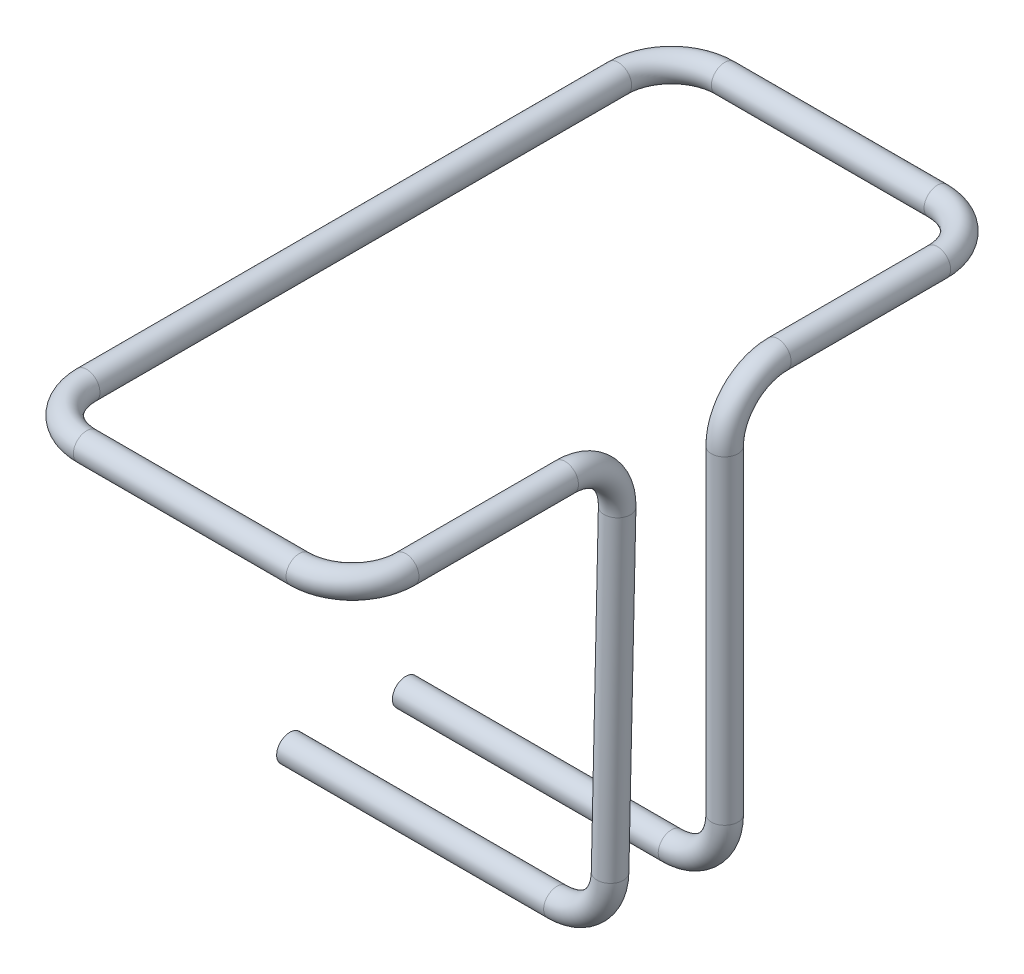
SolidWorks part; units mm, degrees
ref_plane "Front Plane" through (0, 0, 0) normal (0, 0, 1) x (1, 0, 0)
ref_plane "Top Plane" through (0, 0, 0) normal (0, 1, 0) x (1, 0, 0)
ref_plane "Right Plane" through (0, 0, 0) normal (1, 0, 0) x (0, 0, -1)
sketch3d "3DSketch1"
  line L0 (0, 0, 0) -> (2.5109, 0, 0)
  line L1 (3.0108, 0.489, 0) -> (3.0773, 3.4991, 0)
  line L2 (3.0883, 3.999, 0.5) -> (3.0883, 3.999, 2)
  line L3 (2.5883, 3.999, 2.5) -> (0.5883, 3.999, 2.5)
  line L4 (0.0883, 3.999, 2) -> (0.0883, 3.999, -3)
  line L5 (0.5883, 3.999, -3.5) -> (2.5883, 3.999, -3.5)
  line L6 (3.0883, 3.999, -3) -> (3.0883, 3.999, -1.5)
  line L7 (3.0883, 3.499, -1) -> (3.0883, 0.499, -1)
  line L8 (2.5883, -0.001, -1) -> (0.0883, -0.001, -1)
  arc A0 (3.0883, 0.499, -1) -> (2.5883, -0.001, -1) centre (2.5883, 0.499, -1) ccw
  arc A1 (2.5109, 0, 0) -> (3.0108, 0.489, 0) centre (2.5109, 0.5, 0) ccw
  arc A2 (3.0883, 3.999, -1.5) -> (3.0883, 3.499, -1) centre (3.0883, 3.499, -1.5) ccw
  arc A3 (3.0773, 3.4991, 0) -> (3.0883, 3.999, 0.5) centre (3.0773, 3.4991, 0.5) ccw
  arc A4 (3.0883, 3.999, 2) -> (2.5883, 3.999, 2.5) centre (2.5883, 3.999, 2) ccw
  arc A5 (2.5883, 3.999, -3.5) -> (3.0883, 3.999, -3) centre (2.5883, 3.999, -3) ccw
  arc A6 (0.0883, 3.999, -3) -> (0.5883, 3.999, -3.5) centre (0.5883, 3.999, -3) ccw
  arc A7 (0.5883, 3.999, 2.5) -> (0.0883, 3.999, 2) centre (0.5883, 3.999, 2) ccw
  point P13 (3.0883, -0.001, -1)
  point P14 (2.5883, 0.499, -1.5)
  point P17 (3, 0, 0)
  point P18 (2.5109, 0.5, 0.5)
  point P21 (3.0883, 3.999, -1)
  point P22 (3.5883, 3.499, -1.5)
  point P25 (3.0883, 3.999, 0)
  point P26 (3.5772, 3.4881, 0.5)
  point P29 (3.0883, 3.999, 2.5)
  point P30 (2.5883, 3.499, 2)
  point P33 (3.0883, 3.999, -3.5)
  point P34 (2.5883, 3.499, -3)
  point P37 (0.0883, 3.999, -3.5)
  point P38 (0.5883, 3.499, -3)
  point P41 (0.0883, 3.999, 2.5)
  point P42 (0.5883, 3.499, 2)
  dimension "D10" = 0.5
  dimension "D1" = 3
  dimension "D2" = 4
  dimension "D3" = 2.5
  dimension "D4" = 3
  dimension "D5" = 6
  dimension "D6" = 3
  dimension "D7" = 2.5
  dimension "D8" = 4
  dimension "D9" = 3
sketch "Sketch1" plane through (0, 0, 0) normal (1, 0, 0) x (0, 0, -1)
  circle A0 centre (0, 0) radius 0.125
  dimension "D1" = 0.25
sweep "Sweep1" add profiles "Sketch1" path "3DSketch1"
